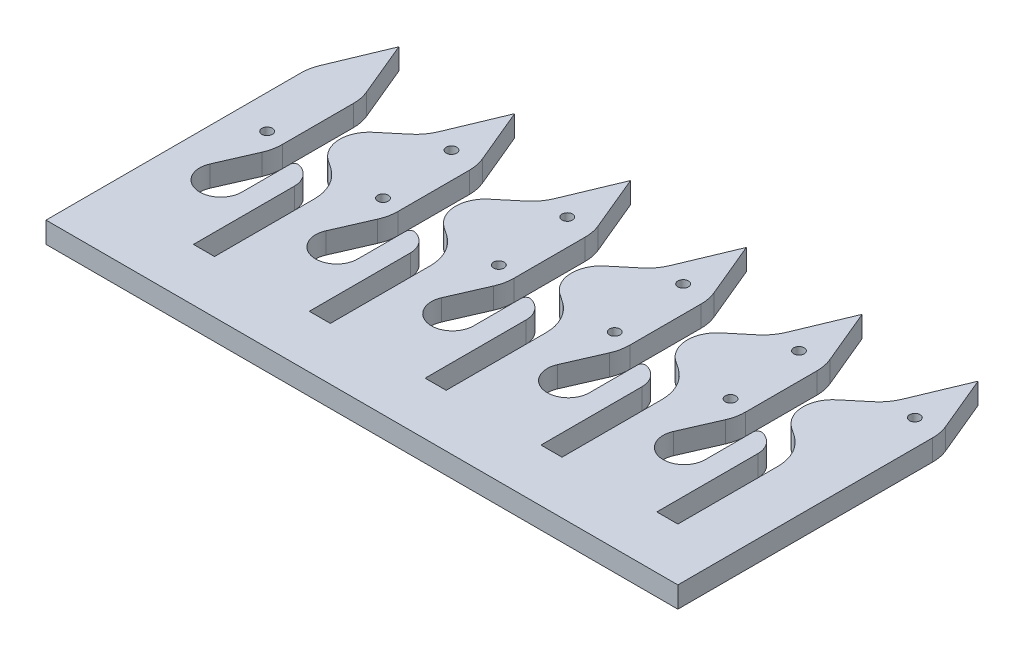
SolidWorks part; units mm, degrees
material "ABS"
ref_plane "Front Plane" through (0, 0, 0) normal (0, 0, 1) x (1, 0, 0)
ref_plane "Top Plane" through (0, 0, 0) normal (0, 1, 0) x (1, 0, 0)
ref_plane "Right Plane" through (0, 0, 0) normal (1, 0, 0) x (0, 0, -1)
sketch "Sketch1" plane through (0, 0, 0) normal (0, 1, 0) x (1, 0, 0)
  line L0 (-371.2073, 45) -> (137.2591, 45) construction
  line L1 (-371.2073, 155) -> (137.2591, 155) construction
  line L2 (-371.2073, 125) -> (137.2591, 125) construction
  line L5 (-371.2073, 25) -> (137.2591, 25) construction
  line L44 (137.2591, 0) -> (-371.2073, 0) construction
  line L45 (0, 0) -> (0, 226.1062) construction
  line L46 (-12.5, -27.5698) -> (-12.5, 226.1062) construction
  line L47 (0, 0) -> (0, 125)
  line L48 (0, 125) -> (-12.5, 155)
  line L49 (-12.5, 155) -> (-25, 125)
  line L50 (-25, 125) -> (-38.4749, 113.7449)
  line L51 (-25, 25) -> (-25, 83)
  line L52 (-25, 83) -> (-37.3786, 91.4273)
  line L53 (-25, 25) -> (-35, 25)
  line L54 (-35, 25) -> (-35, 73)
  line L55 (-45, 83) -> (-45, 58)
  line L56 (-55, 83) -> (-55, 125)
  line L57 (-55, 83) -> (-64.1652, 62)
  line L58 (-67.5, 155) -> (-80, 125)
  line L59 (-55, 125) -> (-67.5, 155)
  line L60 (-80, 125) -> (-93.4749, 113.7449)
  line L61 (-80, 83) -> (-92.3786, 91.4273)
  line L62 (-80, 25) -> (-80, 83)
  line L63 (-90, 25) -> (-90, 73)
  line L64 (-80, 25) -> (-90, 25)
  line L65 (-100, 83) -> (-100, 58)
  line L66 (-110, 83) -> (-119.1652, 62)
  line L67 (-110, 83) -> (-110, 125)
  line L68 (-122.5, 155) -> (-135, 125)
  line L69 (-110, 125) -> (-122.5, 155)
  line L70 (-135, 125) -> (-148.4749, 113.7449)
  line L71 (-135, 83) -> (-147.3786, 91.4273)
  line L72 (-135, 25) -> (-135, 83)
  line L73 (-145, 25) -> (-145, 73)
  line L74 (-135, 25) -> (-145, 25)
  line L75 (-155, 83) -> (-155, 58)
  line L76 (-165, 83) -> (-174.1652, 62)
  line L77 (-165, 83) -> (-165, 125)
  line L78 (-177.5, 155) -> (-190, 125)
  line L79 (-165, 125) -> (-177.5, 155)
  line L80 (-190, 125) -> (-203.4749, 113.7449)
  line L81 (-190, 83) -> (-202.3786, 91.4273)
  line L82 (-190, 25) -> (-190, 83)
  line L83 (-200, 25) -> (-200, 73)
  line L84 (-190, 25) -> (-200, 25)
  line L85 (-210, 83) -> (-210, 58)
  line L86 (-220, 83) -> (-229.1652, 62)
  line L87 (-220, 83) -> (-220, 125)
  line L88 (-232.5, 155) -> (-245, 125)
  line L89 (-220, 125) -> (-232.5, 155)
  line L90 (-245, 125) -> (-258.4749, 113.7449)
  line L91 (-245, 83) -> (-257.3786, 91.4273)
  line L92 (-245, 25) -> (-245, 83)
  line L93 (-255, 25) -> (-255, 73)
  line L94 (-245, 25) -> (-255, 25)
  line L95 (-265, 83) -> (-265, 58)
  line L96 (-275, 83) -> (-284.1652, 62)
  line L97 (-275, 83) -> (-275, 125)
  line L98 (-287.5, 155) -> (-300, 125)
  line L99 (-275, 125) -> (-287.5, 155)
  line L103 (0, 0) -> (-300, 0)
  line L104 (-300, 0) -> (-300, 125)
  line L108 (-320, 83) -> (-320, 58) [skipped]
  line L109 (-330, 83) -> (-339.1652, 62) [skipped]
  line L110 (-330, 83) -> (-330, 125) [skipped]
  line L111 (-300, 125) -> (-313.4749, 113.7449) [skipped]
  line L112 (-300, 83) -> (-312.3786, 91.4273) [skipped]
  line L113 (-300, 25) -> (-300, 83) [skipped]
  line L114 (-310, 25) -> (-310, 73) [skipped]
  line L115 (-300, 25) -> (-310, 25) [skipped]
  arc A10 (-38.4749, 113.7449) -> (-37.3786, 91.4273) centre (-29.5, 103) ccw
  arc A11 (-35, 73) -> (-45, 83) centre (-45, 73) ccw
  arc A12 (-64.1652, 62) -> (-45, 58) centre (-55, 58) ccw
  arc A13 (-93.4749, 113.7449) -> (-92.3786, 91.4273) centre (-84.5, 103) ccw
  arc A14 (-90, 73) -> (-100, 83) centre (-100, 73) ccw
  arc A15 (-119.1652, 62) -> (-100, 58) centre (-110, 58) ccw
  arc A16 (-148.4749, 113.7449) -> (-147.3786, 91.4273) centre (-139.5, 103) ccw
  arc A17 (-145, 73) -> (-155, 83) centre (-155, 73) ccw
  arc A18 (-174.1652, 62) -> (-155, 58) centre (-165, 58) ccw
  arc A19 (-203.4749, 113.7449) -> (-202.3786, 91.4273) centre (-194.5, 103) ccw
  arc A20 (-200, 73) -> (-210, 83) centre (-210, 73) ccw
  arc A21 (-229.1652, 62) -> (-210, 58) centre (-220, 58) ccw
  arc A22 (-258.4749, 113.7449) -> (-257.3786, 91.4273) centre (-249.5, 103) ccw
  arc A23 (-255, 73) -> (-265, 83) centre (-265, 73) ccw
  arc A24 (-284.1652, 62) -> (-265, 58) centre (-275, 58) ccw
  circle A25 centre (-12.5, 125) radius 2.5
  circle A26 centre (-64, 89) radius 2.5
  circle A27 centre (-67.5, 125) radius 2.5
  arc A28 (-313.4749, 113.7449) -> (-312.3786, 91.4273) centre (-304.5, 103) ccw [skipped]
  arc A29 (-310, 73) -> (-320, 83) centre (-320, 73) ccw [skipped]
  arc A30 (-339.1652, 62) -> (-320, 58) centre (-330, 58) ccw [skipped]
  circle A31 centre (-119, 89) radius 2.5
  circle A32 centre (-122.5, 125) radius 2.5
  circle A33 centre (-174, 89) radius 2.5
  circle A34 centre (-177.5, 125) radius 2.5
  circle A35 centre (-229, 89) radius 2.5
  circle A36 centre (-232.5, 125) radius 2.5
  circle A37 centre (-284, 89) radius 2.5
  dimension "D7" = 10
  dimension "D8" = 10
  dimension "D9" = 20
  dimension "D12" = 14
  dimension "D18" = 5
  dimension "D19" = 5
  dimension "D2" = 25
  dimension "D3" = 20
  dimension "D4" = 80
  dimension "D5" = 30
  dimension "D6" = 12.5
  dimension "D10" = 13
  dimension "D11" = 10
  dimension "D13" = 22
  dimension "D14" = 17
  dimension "D15" = 300
  dimension "D16" = 58
  dimension "D17" = 6
  dimension "D20" = 9
  dimension "D21" = 36
  dimension "D22" = 5
extrude "Boss-Extrude1" add sketch "Sketch1" along normal blind 10
fillet "Fillet1" radius 20 22 edges at (-300, 5, -125) (0, 5, -125) (-55, 5, -125) (-110, 5, -125) (-165, 5, -125) (-220, 5, -125) (-275, 5, -125) (-245, 5, -83) (-190, 5, -83) (-135, 5, -83) (-80, 5, -83) (-25, 5, -83) (-55, 5, -83) (-110, 5, -83) (-165, 5, -83) (-220, 5, -83) (-275, 5, -83) (-245, 5, -125) (-190, 5, -125) (-135, 5, -125) (-80, 5, -125) (-25, 5, -125)
fillet "Fillet2" radius 2 5 edges at (-45, 5, -83) (-100, 5, -83) (-155, 5, -83) (-210, 5, -83) (-265, 5, -83)
